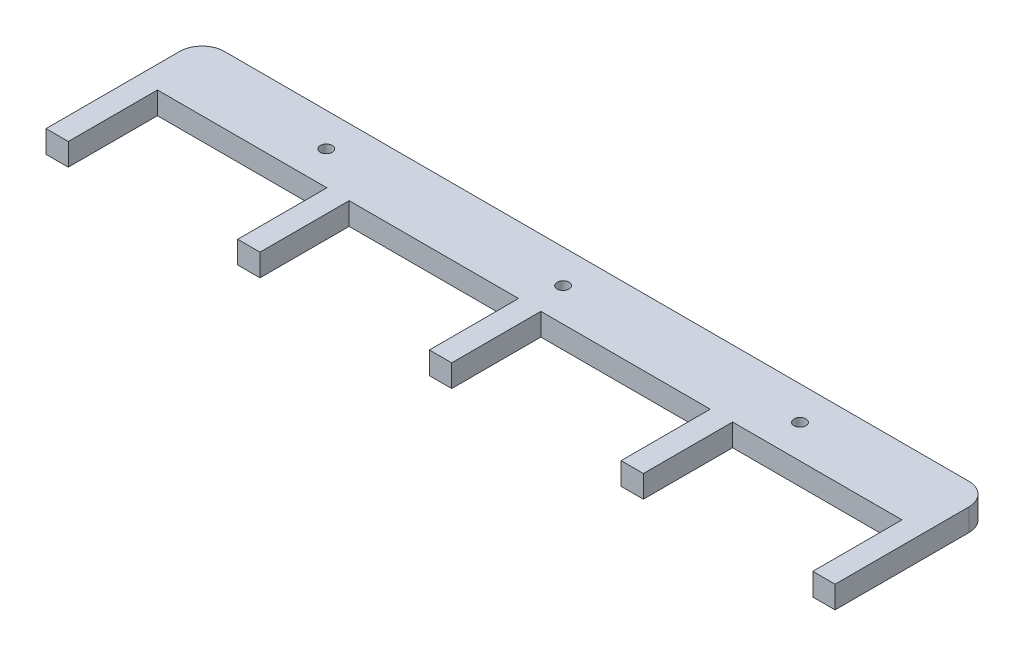
SolidWorks part; units mm, degrees
material "Acrylic (Medium-high impact)"
ref_plane "Front Plane" through (0, 0, 0) normal (0, 0, 1) x (1, 0, 0)
ref_plane "Top Plane" through (0, 0, 0) normal (0, 1, 0) x (1, 0, 0)
ref_plane "Right Plane" through (0, 0, 0) normal (1, 0, 0) x (0, 0, -1)
sketch "Sketch1" plane through (0, 0, 0) normal (0, 1, 0) x (1, 0, 0)
  line L0 (-120.2531, 63.5) -> (-125.3331, 63.5) construction
  line L1 (93.1069, 88.9) -> (-131.6831, 88.9) construction
  line L2 (93.1069, 88.9) -> (93.1069, -88.9) construction
  line L3 (93.1069, -88.9) -> (-131.6831, -88.9) construction
  line L4 (-131.6831, 88.9) -> (-131.6831, -88.9) construction
  line L5 (0, 0) -> (93.1069, 0) construction
  line L6 (-131.6831, 82.55) -> (-131.6831, 44.45)
  line L7 (-131.6831, 44.45) -> (-125.3331, 44.45)
  line L8 (-125.3331, 69.85) -> (-125.3331, 44.45)
  line L9 (-125.3331, 69.85) -> (-77.0731, 69.85)
  line L10 (-77.0731, 44.45) -> (-77.0731, 69.85)
  line L11 (-77.0731, 44.45) -> (-70.7231, 44.45)
  line L12 (-70.7231, 44.45) -> (-70.7231, 69.85)
  line L13 (-70.7231, 69.85) -> (-22.4631, 69.85)
  line L14 (-22.4631, 69.85) -> (-22.4631, 44.45)
  line L15 (-22.4631, 44.45) -> (-16.1131, 44.45)
  line L16 (-16.1131, 44.45) -> (-16.1131, 69.85)
  line L17 (-16.1131, 69.85) -> (32.1469, 69.85)
  line L18 (86.7569, 69.85) -> (86.7569, 44.45)
  line L19 (86.7569, 44.45) -> (93.1069, 44.45)
  line L20 (93.1069, 44.45) -> (93.1069, 82.55)
  line L21 (86.7569, 88.9) -> (-125.3331, 88.9)
  line L22 (32.1469, 69.85) -> (32.1469, 44.45)
  line L23 (32.1469, 44.45) -> (38.4969, 44.45)
  line L24 (38.4969, 44.45) -> (38.4969, 69.85)
  line L25 (38.4969, 69.85) -> (86.7569, 69.85)
  line L26 (-19.2881, 44.45) -> (-19.2881, 19.05) construction
  line L27 (-125.3331, 82.55) -> (-125.3331, 88.9) construction
  line L28 (0, 0) -> (-82.1531, 0) construction
  line L29 (-120.2531, 63.5) -> (-82.1531, 63.5) construction
  line L30 (-120.2531, 63.5) -> (-120.2531, -63.5) construction
  line L31 (-120.2531, -63.5) -> (-82.1531, -63.5) construction
  line L32 (-82.1531, 63.5) -> (-82.1531, -63.5) construction
  line L33 (-101.2031, 63.5) -> (-101.2031, 69.85) construction
  line L35 (93.1069, 79.375) -> (-131.6831, 79.375) construction
  line L36 (-25.7175, 69.85) -> (-25.7175, 79.375) construction
  line L37 (-25.7175, 79.375) -> (-25.7175, 88.9) construction
  line L38 (-82.1531, 63.5) -> (-77.0731, 63.5) construction
  line L39 (-19.2881, 44.45) -> (-19.2881, 79.375) construction
  arc A1 (86.7569, 88.9) -> (93.1069, 82.55) centre (86.7569, 82.55) cw
  arc A2 (-125.3331, 88.9) -> (-131.6831, 82.55) centre (-125.3331, 82.55) ccw
  circle A10 centre (-86.7569, 79.375) radius 1.7
  circle A11 centre (-19.2881, 79.375) radius 1.7
  circle A12 centre (48.1806, 79.375) radius 1.7
  point P0 (0, 0)
  point P58 (-77.0731, 69.85)
  point P61 (-125.3331, 69.85)
  dimension "D8" = 5.08
  dimension "D10" = 3.4
  dimension "D2" = 67.4688
  dimension "D3" = 6.35
  dimension "D4" = 67.4688
  dimension "D5" = 69.85
  dimension "D6" = 38.1
  dimension "D7" = 127
  dimension "D9" = 44.45
  dimension "D11" = 48.26
  dimension "D12" = 48.26
  dimension "D13" = 48.26
  dimension "D14" = 224.79
extrude "Boss-Extrude1" add sketch "Sketch1" along normal blind 6.35
equation "\"D11@Sketch1\"=2*\"D8@Sketch1\"+\"D6@Sketch1\""
equation "\"D12@Sketch1\"=\"D11@Sketch1\""
equation "\"D13@Sketch1\"=\"D11@Sketch1\""
